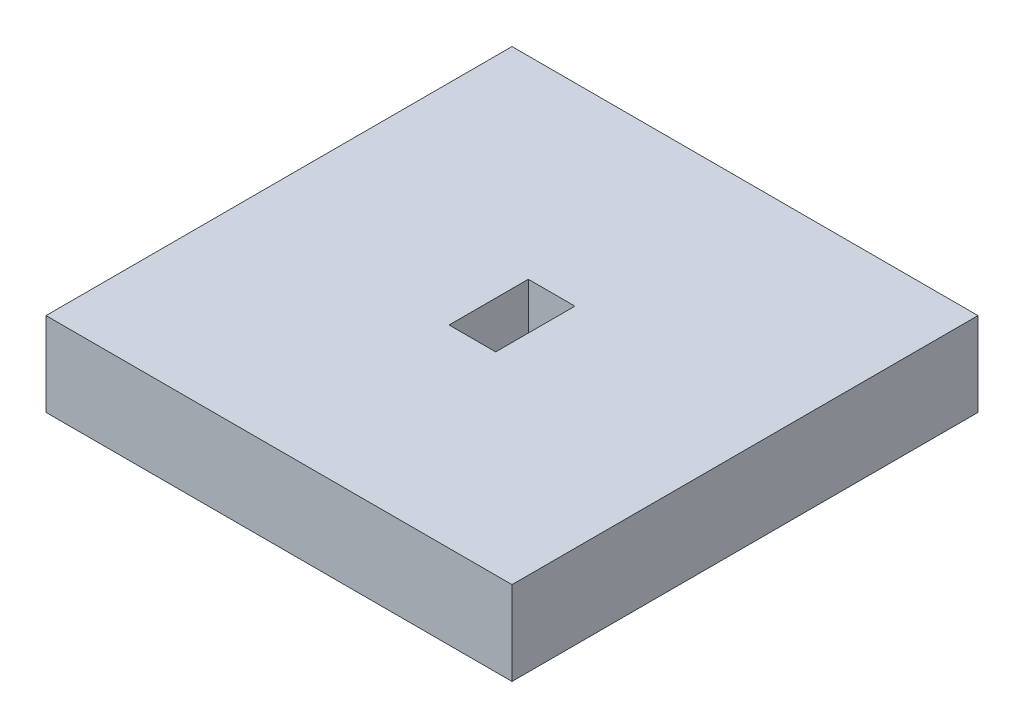
SolidWorks part; units mm, degrees
ref_plane "Спереди" through (0, 0, 0) normal (0, 0, 1) x (1, 0, 0)
ref_plane "Сверху" through (0, 0, 0) normal (0, 1, 0) x (1, 0, 0)
ref_plane "Справа" through (0, 0, 0) normal (1, 0, 0) x (0, 0, -1)
sketch "Эскиз1" plane through (0, 0, 0) normal (0, 1, 0) x (1, 0, 0)
  line L1 (50, -50) -> (-50, -50)
  line L2 (50, -50) -> (50, 50)
  line L3 (50, 50) -> (-50, 50)
  line L4 (-50, -50) -> (-50, 50)
  line L5 (50, -50) -> (-50, 50) construction
  line L6 (50, 50) -> (-50, -50) construction
  point P0 (0, 0)
  dimension "D1" = 100
  dimension "D2" = 100
extrude "Бобышка-Вытянуть1" add sketch "Эскиз1" along normal blind 18
sketch "Эскиз2" plane through (0, 18, 0) normal (0, 1, 0) x (1, 0, 0)
  line L1 (5, -8.5) -> (-5, -8.5)
  line L2 (5, -8.5) -> (5, 8.5)
  line L3 (5, 8.5) -> (-5, 8.5)
  line L4 (-5, -8.5) -> (-5, 8.5)
  line L5 (5, -8.5) -> (-5, 8.5) construction
  line L6 (5, 8.5) -> (-5, -8.5) construction
  point P0 (0, 0)
  dimension "D1" = 10
  dimension "D2" = 17
extrude "Вырез-Вытянуть1" cut sketch "Эскиз2" against normal through all both and the other way through all
